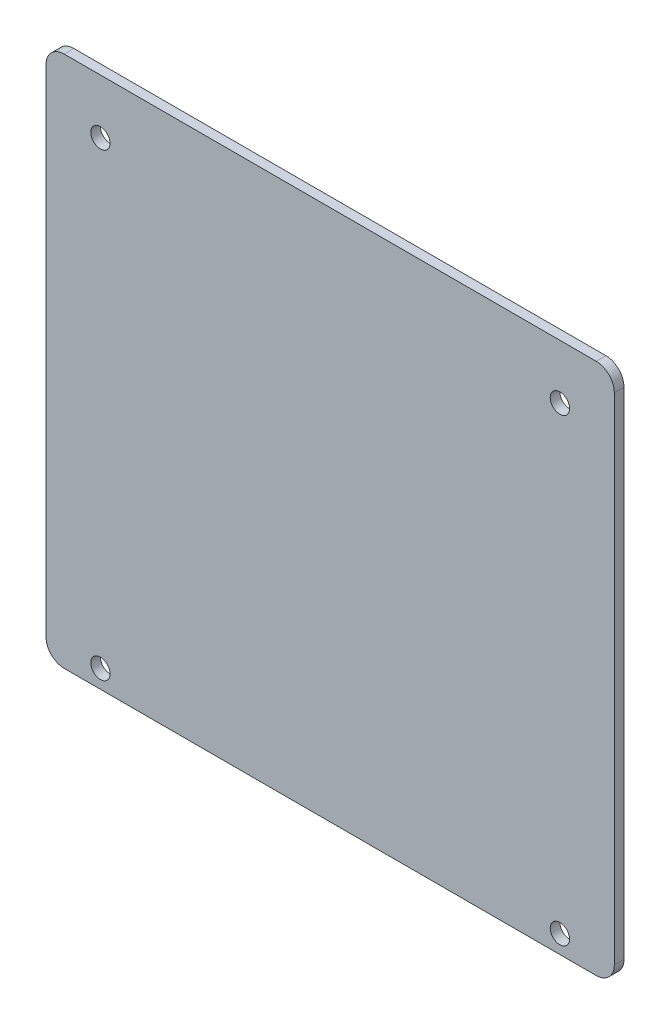
SolidWorks part; units mm, degrees
ref_plane "Front Plane" through (0, 0, 0) normal (0, 0, 1) x (1, 0, 0)
ref_plane "Top Plane" through (0, 0, 0) normal (0, 1, 0) x (1, 0, 0)
ref_plane "Right Plane" through (0, 0, 0) normal (1, 0, 0) x (0, 0, -1)
sketch "Sketch1" plane through (0, 0, 0) normal (0, 0, 1) x (1, 0, 0)
  line L1 (-87.5653, 88.9519) -> (-87.5653, 6.9519)
  line L2 (6.4347, 88.9519) -> (6.4347, 6.9519)
  line L3 (-84.5653, 91.9519) -> (3.4347, 91.9519)
  line L7 (-84.5653, 3.9519) -> (3.4347, 3.9519)
  arc A0 (3.4347, 3.9519) -> (6.4347, 6.9519) centre (3.4347, 6.9519) ccw
  arc A1 (-84.5653, 3.9519) -> (-87.5653, 6.9519) centre (-84.5653, 6.9519) cw
  arc A2 (-84.5653, 91.9519) -> (-87.5653, 88.9519) centre (-84.5653, 88.9519) ccw
  arc A3 (3.4347, 91.9519) -> (6.4347, 88.9519) centre (3.4347, 88.9519) cw
  dimension "D5" = 3
  dimension "D6" = 3
  dimension "D9" = 88
  dimension "D10" = 3
  dimension "D4" = 3
  dimension "D2" = 88
  dimension "D3" = 94
extrude "Boss-Extrude1" add sketch "Sketch1" along normal blind 1.6
hole_wizard "Ø3.2 (3.2) Diameter Hole3" positions "Sketch7" profile "Sketch6" hole size "Ø3.2" standard "Ansi Metric" end condition up to next
sketch "Sketch7" plane through (0, 0, 0) normal (0, 0, -1) x (-1, 0, 0)
  line L2 (-6.4347, 6.9519) -> (-6.4347, 88.9519) construction
  line L3 (84.5653, 3.9519) -> (-3.4347, 3.9519) construction
  line L4 (87.5653, 47.9519) -> (-6.4347, 47.9519) construction
  line L5 (87.5653, 88.9519) -> (87.5653, 6.9519) construction
  line L6 (40.5653, 91.9519) -> (40.5653, 3.9519) construction
  line L7 (-3.4347, 91.9519) -> (84.5653, 91.9519) construction
  point P6 (78.5653, 6.9519)
  point P9 (78.5653, 82.9519)
  point P12 (2.5653, 82.9519)
  point P15 (2.5653, 6.9519)
  point P41 (63.3889, 2.8539)
  dimension "D1" = 35
  dimension "D2" = 38
  dimension "D3" = 38
  dimension "D4" = 35
  dimension "D5" = 41
  dimension "D6" = 38
  dimension "D7" = 38
sketch "Sketch6" plane through (-78.5653, 6.9519, 0) normal (1, 0, 0) x (0, 1, 0)
  line L0 (0, 0) -> (0, 1.6)
  line L1 (0, 1.6) -> (1.6, 1.6)
  line L2 (1.6, 1.6) -> (1.6, 0)
  line L5 (1.6, 0) -> (0, 0)
  line L11 (0, -6.35) -> (0, 107.95) construction
  dimension "Thru Hole Dia." = 3.2
  dimension "Thru Hole Depth" = 1.6
